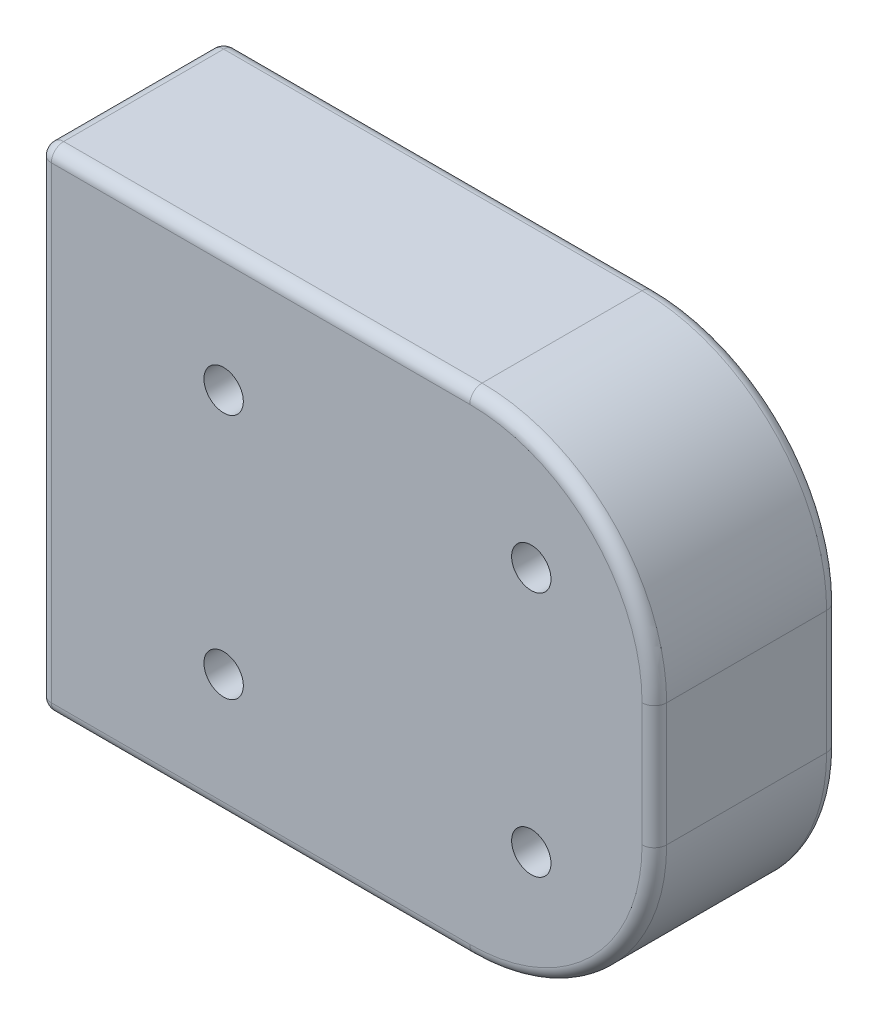
SolidWorks part; units mm, degrees
ref_plane "前视基准面" through (0, 0, 0) normal (0, 0, 1) x (1, 0, 0)
ref_plane "上视基准面" through (0, 0, 0) normal (0, 1, 0) x (1, 0, 0)
ref_plane "右视基准面" through (0, 0, 0) normal (1, 0, 0) x (0, 0, -1)
sketch "草图1" plane through (0, 0, 0) normal (0, 0, 1) x (1, 0, 0)
  line L1 (-25, -20) -> (25, -20)
  line L2 (-25, -20) -> (-25, 20)
  line L3 (-25, 20) -> (25, 20)
  line L4 (25, -20) -> (25, 20)
  line L5 (-25, -20) -> (25, 20) construction
  line L6 (-25, 20) -> (25, -20) construction
  point P0 (0, 0)
  dimension "D1" = 40
  dimension "D2" = 50
extrude "凸台-拉伸1" add sketch "草图1" along normal blind 15
sketch "草图2" plane through (0, 0, 15) normal (0, 0, 1) x (1, 0, 0)
  line L0 (0, 0) -> (50000, 0) construction
  line L7 (-10, -10) -> (-10, 10) construction
  line L8 (-10, 10) -> (15, 10) construction
  line L9 (15, -10) -> (15, 10) construction
  line L10 (-10, -10) -> (15, 10) construction
  line L11 (-10, 10) -> (15, -10) construction
  line L12 (2.5, 0) -> (2.5, 50000) construction
  line L13 (-10, -10) -> (15, -10) construction
  circle A4 centre (-10, 10) radius 1.6
  circle A5 centre (15, 10) radius 1.6
  circle A6 centre (15, -10) radius 1.6
  circle A7 centre (-10, -10) radius 1.6
  point P0 (2.5, 0)
  dimension "D3" = 2.5
  dimension "D4" = 3.2
  dimension "D1" = 20
  dimension "D2" = 25
extrude "切除-拉伸1" cut sketch "草图2" against normal through all
fillet "圆角1" radius 15 2 edges at (25, -20, 7.5) (25, 20, 7.5)
fillet "圆角2" radius 1 2 edges at (-25, -20, 7.5) (-25, 20, 7.5)
fillet "圆角3" radius 1 16 edges at (20.6066, 15.6066, 0) (25, 0, 0) (20.6066, -15.6066, 0) (-7, -20, 0) (-24.7071, -19.7071, 0) (-25, 0, 0) (-24.7071, 19.7071, 0) (20.6066, 15.6066, 15) (25, 0, 15) (20.6066, -15.6066, 15) (-7, -20, 15) (-24.7071, -19.7071, 15) (-25, 0, 15) (-24.7071, 19.7071, 15) (-7, 20, 0) (-7, 20, 15)
equation "\"3。2\"=3.16193"
